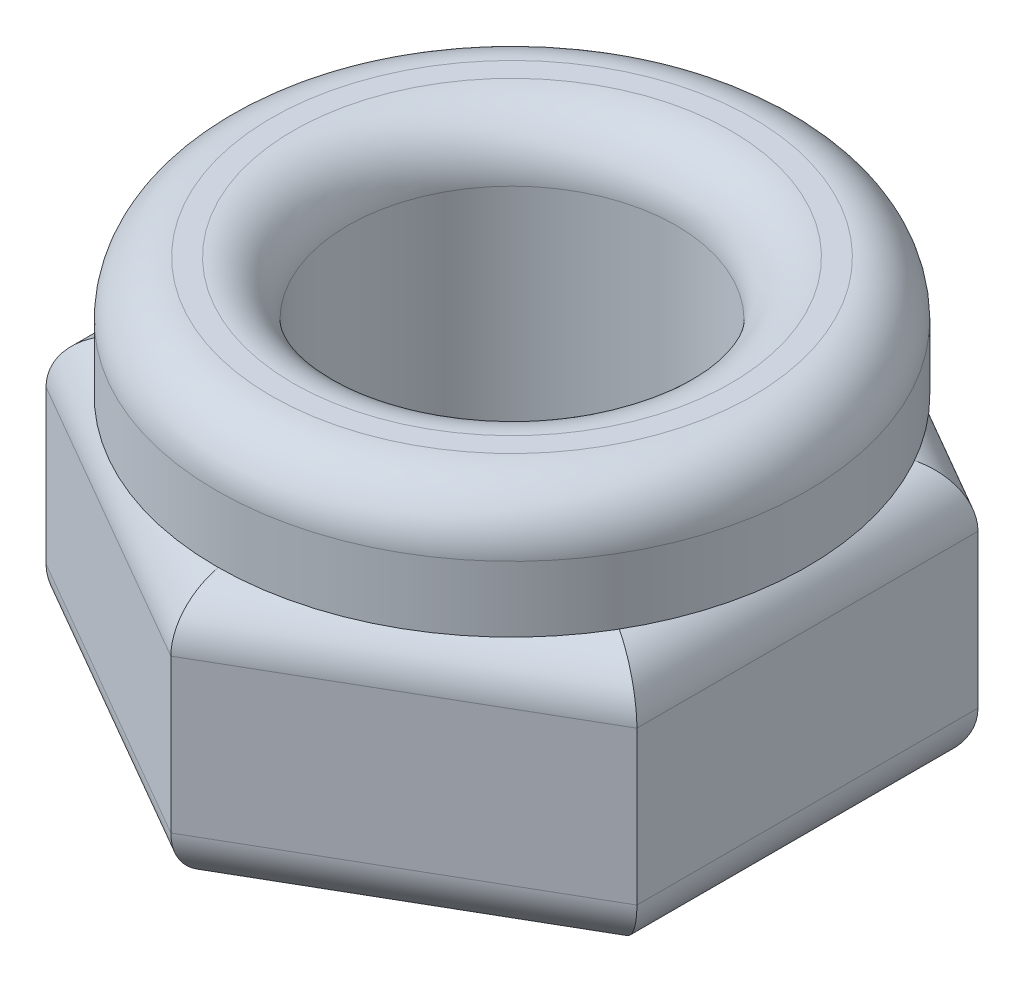
SolidWorks part; units mm, degrees
ref_plane "前视基准面" through (0, 0, 0) normal (0, 0, 1) x (1, 0, 0)
ref_plane "上视基准面" through (0, 0, 0) normal (0, 1, 0) x (1, 0, 0)
ref_plane "右视基准面" through (0, 0, 0) normal (1, 0, 0) x (0, 0, -1)
sketch "草图1" plane through (0, 0, 0) normal (0, 1, 0) x (1, 0, 0)
  line L1 (0, 3.1177) -> (-2.7, 1.5588)
  line L2 (-2.7, 1.5588) -> (-2.7, -1.5588)
  line L3 (-2.7, -1.5588) -> (0, -3.1177)
  line L4 (0, -3.1177) -> (2.7, -1.5588)
  line L5 (2.7, -1.5588) -> (2.7, 1.5588)
  line L6 (2.7, 1.5588) -> (0, 3.1177)
  circle A0 centre (0, 0) radius 2.7 construction
  dimension "D1" = 5.4
extrude "凸台-拉伸1" add sketch "草图1" along normal blind 2.4
sketch "草图2" plane through (0, 2.4, 0) normal (0, 1, 0) x (1, 0, 0)
  line L6 (2.7, 1.5588) -> (0, 3.1177)
  line L7 (0, 3.1177) -> (-2.7, 1.5588)
  line L8 (-2.7, 1.5588) -> (-2.7, -1.5588)
  line L9 (-2.7, -1.5588) -> (0, -3.1177)
  line L10 (0, -3.1177) -> (2.7, -1.5588)
  line L11 (2.7, -1.5588) -> (2.7, 1.5588)
  line L12 (2.7, 1.5588) -> (0, 3.1177)
  line L13 (0, 3.1177) -> (-2.7, 1.5588)
  line L14 (-2.7, 1.5588) -> (-2.7, -1.5588)
  line L15 (-2.7, -1.5588) -> (0, -3.1177)
  line L16 (0, -3.1177) -> (2.7, -1.5588)
  line L17 (2.7, -1.5588) -> (2.7, 1.5588)
  circle A0 centre (0, 0) radius 1.5
  dimension "D2" = 3
  dimension "D1" = 0
extrude "切除-拉伸1" cut sketch "草图2" against normal blind 10 contours A0
fillet "圆角1" radius 0.5 12 edges at (1.35, 0, 2.3383) (2.7, 0, 0) (1.35, 0, -2.3383) (-1.35, 0, -2.3383) (-2.7, 0, 0) (-1.35, 0, 2.3383) (-1.35, 2.4, 2.3383) (-2.7, 2.4, 0) (-1.35, 2.4, -2.3383) (1.35, 2.4, -2.3383) (2.7, 2.4, 0) (1.35, 2.4, 2.3383)
sketch "草图3" plane through (0, 2.4, 0) normal (0, 1, 0) x (1, 0, 0)
  line L0 (0, 3.1177) -> (-2.7, 1.5588) construction
  line L1 (-2.2, 1.2702) -> (0, 2.5403) construction
  line L2 (-2.7, 1.5588) -> (-2.7, -1.5588) construction
  line L3 (-2.2, -1.2702) -> (-2.2, 1.2702) construction
  line L4 (-2.7, -1.5588) -> (0, -3.1177) construction
  line L5 (0, -2.5403) -> (-2.2, -1.2702) construction
  line L6 (2.2, -1.2702) -> (0, -2.5403) construction
  line L7 (0, -3.1177) -> (2.7, -1.5588) construction
  line L8 (2.2, 1.2702) -> (2.2, -1.2702) construction
  line L9 (2.7, -1.5588) -> (2.7, 1.5588) construction
  line L10 (2.7, 1.5588) -> (0, 3.1177) construction
  line L11 (0, 2.5403) -> (2.2, 1.2702) construction
  line L12 (0, 3.1177) -> (-2.7, 1.5588)
  line L13 (-2.2, 1.2702) -> (0, 2.5403)
  line L14 (-2.7, 1.5588) -> (-2.7, -1.5588)
  line L15 (-2.2, -1.2702) -> (-2.2, 1.2702)
  line L16 (-2.7, -1.5588) -> (0, -3.1177)
  line L17 (0, -2.5403) -> (-2.2, -1.2702)
  line L18 (2.2, -1.2702) -> (0, -2.5403)
  line L19 (0, -3.1177) -> (2.7, -1.5588)
  line L20 (2.2, 1.2702) -> (2.2, -1.2702)
  line L21 (2.7, -1.5588) -> (2.7, 1.5588)
  line L22 (2.7, 1.5588) -> (0, 3.1177)
  line L23 (0, 2.5403) -> (2.2, 1.2702)
  circle A0 centre (0, 0) radius 2.7
  circle A1 centre (0, 0) radius 1.5
extrude "凸台-拉伸2" add sketch "草图3" along normal blind 1.1
fillet "圆角2" radius 0.5 2 edges at (0, 3.5, 1.5) (0, 3.5, 2.7)
sketch "草图4" [suppressed] plane through (0, 2.9, 0) normal (0, 1, 0) x (1, 0, 0)
  line L0 (0, 3.926) -> (-3.4, 1.963) construction
  line L1 (-2.9, 1.6743) -> (0, 3.3486) construction
  line L2 (-3.4, 1.963) -> (-3.4, -1.963) construction
  line L3 (-2.9, -1.6743) -> (-2.9, 1.6743) construction
  line L4 (-3.4, -1.963) -> (0, -3.926) construction
  line L5 (0, -3.3486) -> (-2.9, -1.6743) construction
  line L6 (2.9, -1.6743) -> (0, -3.3486) construction
  line L7 (0, -3.926) -> (3.4, -1.963) construction
  line L8 (2.9, 1.6743) -> (2.9, -1.6743) construction
  line L9 (3.4, -1.963) -> (3.4, 1.963) construction
  line L10 (3.4, 1.963) -> (0, 3.926) construction
  line L11 (0, 3.3486) -> (2.9, 1.6743) construction
  line L12 (0, 3.926) -> (-3.4, 1.963)
  line L13 (-2.9, 1.6743) -> (0, 3.3486)
  line L14 (-3.4, 1.963) -> (-3.4, -1.963)
  line L15 (-2.9, -1.6743) -> (-2.9, 1.6743)
  line L16 (-3.4, -1.963) -> (0, -3.926)
  line L17 (0, -3.3486) -> (-2.9, -1.6743)
  line L18 (2.9, -1.6743) -> (0, -3.3486)
  line L19 (0, -3.926) -> (3.4, -1.963)
  line L20 (2.9, 1.6743) -> (2.9, -1.6743)
  line L21 (3.4, -1.963) -> (3.4, 1.963)
  line L22 (3.4, 1.963) -> (0, 3.926)
  line L23 (0, 3.3486) -> (2.9, 1.6743)
  circle A0 centre (0, 0) radius 3.4
  circle A1 centre (0, 0) radius 2
  dimension "D1" = 4
extrude "凸台-拉伸3" [suppressed] add sketch "草图4" along normal blind 1.9
fillet "圆角3" [suppressed] radius 0.5
